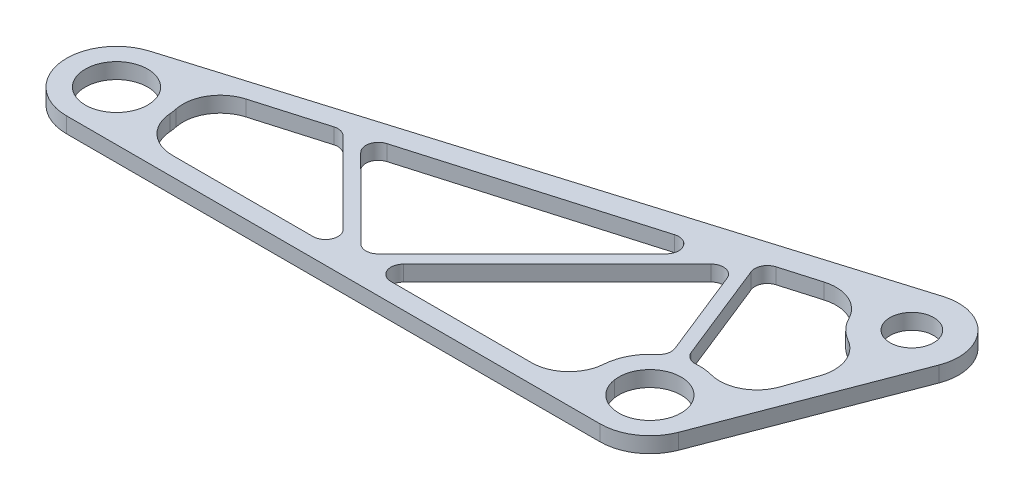
SolidWorks part; units mm, degrees
material "6061-T6 (SS)"
ref_plane "Front Plane" through (0, 0, 0) normal (0, 0, 1) x (1, 0, 0)
ref_plane "Top Plane" through (0, 0, 0) normal (0, 1, 0) x (1, 0, 0)
ref_plane "Right Plane" through (0, 0, 0) normal (1, 0, 0) x (0, 0, -1)
sketch "Sketch1" plane through (0, 0, 0) normal (0, 1, 0) x (1, 0, 0)
  line L0 (0, 0) -> (123.8103, 38.1) construction
  line L1 (123.8103, 38.1) -> (108.585, 0) construction
  line L2 (108.585, 0) -> (0, 0) construction
  line L3 (-2.9406, 9.7251) -> (121.0535, 47.2173)
  line L4 (0, -10.16) -> (108.585, -10.16)
  line L5 (118.0768, -3.6237) -> (132.7089, 34.7027)
  line L6 (108.585, 0) -> (109.9814, -10.0636) construction
  line L7 (-1.7782, 6.0959) -> (122.5656, 42.3672)
  line L8 (114.5847, -2.0801) -> (128.0101, 36.644)
  line L9 (108.585, -6.35) -> (0, -6.35)
  line L10 (108.585, 0) -> (94.883, 34.2921) construction
  line L11 (108.585, 0) -> (108.585, 33.4147) construction
  line L12 (96.1079, 34.6494) -> (106.0241, 9.832)
  line L13 (93.6581, 33.9348) -> (103.6654, 8.8895)
  line L14 (94.883, 34.2921) -> (54.2925, -6.35) construction
  line L15 (54.2925, -6.35) -> (31.973, 15.9412) construction
  line L16 (31.973, 15.9412) -> (7.9311, -6.35) construction
  line L17 (92.3502, 33.5533) -> (52.4976, -6.35)
  line L18 (56.0874, -6.35) -> (97.4158, 35.0309)
  line L19 (56.0897, -6.35) -> (33.3639, 16.3469)
  line L20 (52.4953, -6.35) -> (30.582, 15.5355)
  circle A0 centre (0, 0) radius 6.35
  circle A1 centre (123.8103, 38.1) radius 4.445
  circle A2 centre (108.585, 0) radius 6.35
  circle A3 centre (0, 0) radius 10.16
  circle A4 centre (108.585, 0) radius 10.16
  circle A5 centre (123.8103, 38.1) radius 9.525
  arc A6 (-2.9406, 9.7251) -> (0, -10.16) centre (0, 0) ccw
  arc A7 (118.0768, -3.6237) -> (108.585, -10.16) centre (108.585, 0) cw
  arc A8 (121.0535, 47.2173) -> (132.7089, 34.7027) centre (123.8103, 38.1) cw
  point P35 (0, 0)
  point P44 (0, 0)
  dimension "D4" = 12.7
  dimension "D5" = 12.7
  dimension "D6" = 8.89
  dimension "D1" = 129.54
  dimension "D2" = 38.1
  dimension "D3" = 108.585
  dimension "D7" = 3.81
  dimension "D9" = 5.08
  dimension "D10" = 97.9
  dimension "D8" = 3.81
  dimension "D11" = 21.78
  dimension "D12" = 1.27
  dimension "D13" = 1.27
  dimension "D14" = 1.27
  dimension "D15" = 1.27
  dimension "D16" = 1.27
  dimension "D17" = 1.27
extrude "Boss-Extrude4" add sketch "Sketch1" against normal blind 3.175
ref_plane "Plane1" through (108.585, 0, 0) normal (0.1374, 0, 0.9905) x (0.9905, 0, -0.1374)
split line "Split Line1"
sketch "Sketch2" [suppressed] plane through (0, -3.175, 0) normal (0, -1, 0) x (1, 0, 0)
  line L1 (69.4473, -23.6659) -> (60.7288, -1.2641)
  line L2 (62.8949, 2.1892) -> (101.6127, 5.2609)
  line L3 (101.2476, -37.8411) -> (79.7056, -31.0891)
  line L4 (79.2148, -26.4545) -> (98.3531, -15.6299)
  line L5 (59.9072, -25.992) -> (7.538, -8.592)
  line L6 (63.0965, -22.7173) -> (54.4829, 1.0899)
  line L7 (51.7805, 2.7463) -> (11.1946, -2.3078)
  line L8 (73.1912, -24.8791) -> (102.155, -6.1958)
  line L9 (104.5239, -35.0732) -> (102.1201, -17.4966)
  circle A0 centre (111.76, 0) radius 11.43 construction
  circle A3 centre (0, 0) radius 11.43 construction
  arc A4 (11.1946, -2.3078) -> (7.538, -8.592) centre (0, 0) cw
  arc A5 (101.6127, 5.2609) -> (102.155, -6.1958) centre (111.76, 0) ccw
  arc A6 (101.2476, -37.8411) -> (104.5239, -35.0732) centre (102.0073, -35.4173) ccw
  arc A7 (98.3531, -15.6299) -> (102.1201, -17.4966) centre (99.6035, -17.8407) cw
  arc A8 (69.4473, -23.6659) -> (73.1912, -24.8791) centre (71.8144, -22.7446) ccw
  arc A9 (60.7288, -1.2641) -> (62.8949, 2.1892) centre (63.0958, -0.3428) cw
  arc A10 (63.0965, -22.7173) -> (59.9072, -25.992) centre (60.7081, -23.5815) cw
  arc A11 (54.4829, 1.0899) -> (51.7805, 2.7463) centre (52.0944, 0.2257) ccw
  arc A12 (79.2148, -26.4545) -> (79.7056, -31.0891) centre (80.4653, -28.6654) ccw
  dimension "D1" = 2.54
  dimension "D2" = 2.54
  dimension "D3" = 2.54
  dimension "D4" = 2.54
  dimension "D5" = 2.54
  dimension "D6" = 2.54
  dimension "D7" = 2.54
extrude "Cut-Extrude2" [suppressed] cut sketch "Sketch2" against normal through all
fillet "Fillet1" radius 7.62 6 edges at (100.6539, -1.5875, 6.35) (117.1826, -1.5875, -5.4135) (125.2506, -1.5875, -28.6845) (114.4784, -1.5875, -40.0081) (7.9311, -1.5875, 6.35) (5.8356, -1.5875, -8.3169)
fillet "Fillet2" radius 2.54 10 edges at (30.582, -1.5875, -15.5355) (33.3639, -1.5875, -16.3469) (52.4953, -1.5875, 6.35) (54.2914, -1.5875, 4.5539) (56.0874, -1.5875, 6.35) (92.3502, -1.5875, -33.5533) (94.4191, -1.5875, -32.0304) (103.6654, -1.5875, -8.8895) (106.0241, -1.5875, -9.832) (96.1079, -1.5875, -34.6494)
equation "\"x\"= .05"
equation "\"D15@Sketch1\"=\"x\""
equation "\"D14@Sketch1\"=\"x\""
equation "\"D12@Sketch1\"=\"x\""
equation "\"D13@Sketch1\"=\"x\""
equation "\"D16@Sketch1\"=\"x\""
equation "\"D17@Sketch1\"=\"x\""
